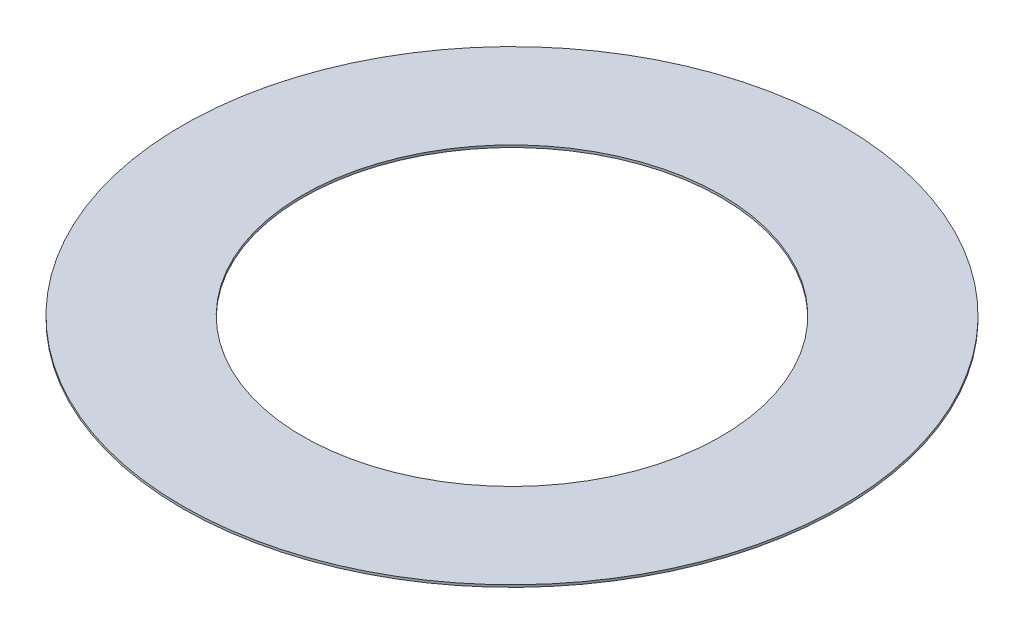
SolidWorks part; units mm, degrees
material "Plain Carbon Steel"
ref_plane "Front Plane" through (0, 0, 0) normal (0, 0, 1) x (1, 0, 0)
ref_plane "Top Plane" through (0, 0, 0) normal (0, 1, 0) x (1, 0, 0)
ref_plane "Right Plane" through (0, 0, 0) normal (1, 0, 0) x (0, 0, -1)
sketch "Sketch1" plane through (0, 0, 0) normal (0, 0, 1) x (1, 0, 0)
  line L0 (-109.5, 8.1325) -> (-109.5, 7.3725) construction
  line L1 (-69.5, 7.3725) -> (-109.5, 7.3725) construction
  line L2 (-69.5, 8.1325) -> (-69.5, 7.3725) construction
  line L3 (-69.5, 8.1325) -> (-109.5, 8.1325) construction
  line L4 (-109.5, 8.1325) -> (-109.5, 7.3725)
  line L5 (-69.5, 7.3725) -> (-109.5, 7.3725)
  line L6 (-69.5, 8.1325) -> (-69.5, 7.3725)
  line L7 (-69.5, 8.1325) -> (-109.5, 8.1325)
  line L8 (0, -200069.0475) -> (0, 200086.9028) construction
  line L9 (0, -200069.0475) -> (0, 200086.9028) construction
revolve "Revolve1" add sketch "Sketch1" angle 360 about L9
